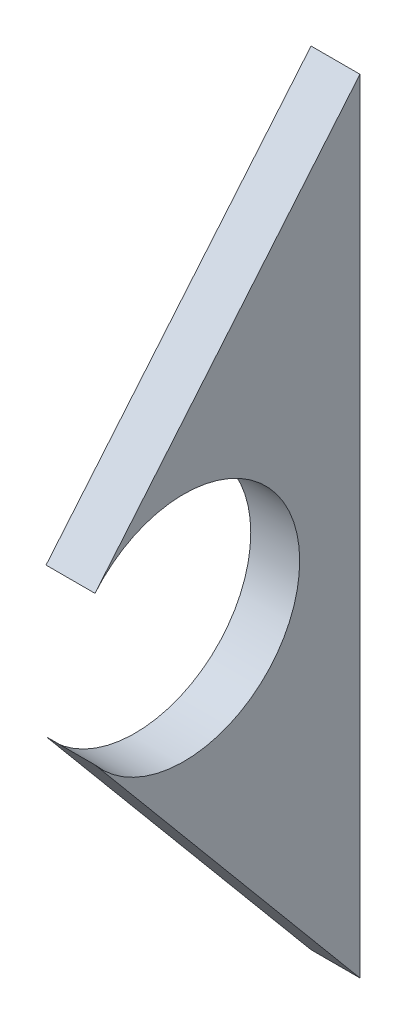
SolidWorks part; units mm, degrees
material "Beech"
ref_plane "Front Plane" through (0, 0, 0) normal (0, 0, 1) x (1, 0, 0)
ref_plane "Top Plane" through (0, 0, 0) normal (0, 1, 0) x (1, 0, 0)
ref_plane "Right Plane" through (0, 0, 0) normal (1, 0, 0) x (0, 0, -1)
sketch "Sketch1" plane through (0, 0, 0) normal (1, 0, 0) x (0, 0, -1)
  line L0 (-1000, 0) -> (49000, 0) construction
  line L1 (0, -1000) -> (0, 49000) construction
  line L2 (-2.8844, 2.4107) -> (5.715, 12.7)
  line L3 (5.715, 12.7) -> (5.715, -12.7)
  line L4 (5.715, -12.7) -> (-2.8844, -2.4107)
  arc A0 (-2.8844, -2.4107) -> (-2.8844, 2.4107) centre (0, 0) ccw
  point P3 (5.715, 0)
  dimension "D1" = 7.5184
  dimension "D2" = 25.4
  dimension "D3" = 5.715
extrude "Boss-Extrude1" add sketch "Sketch1" along normal blind 1.5875
